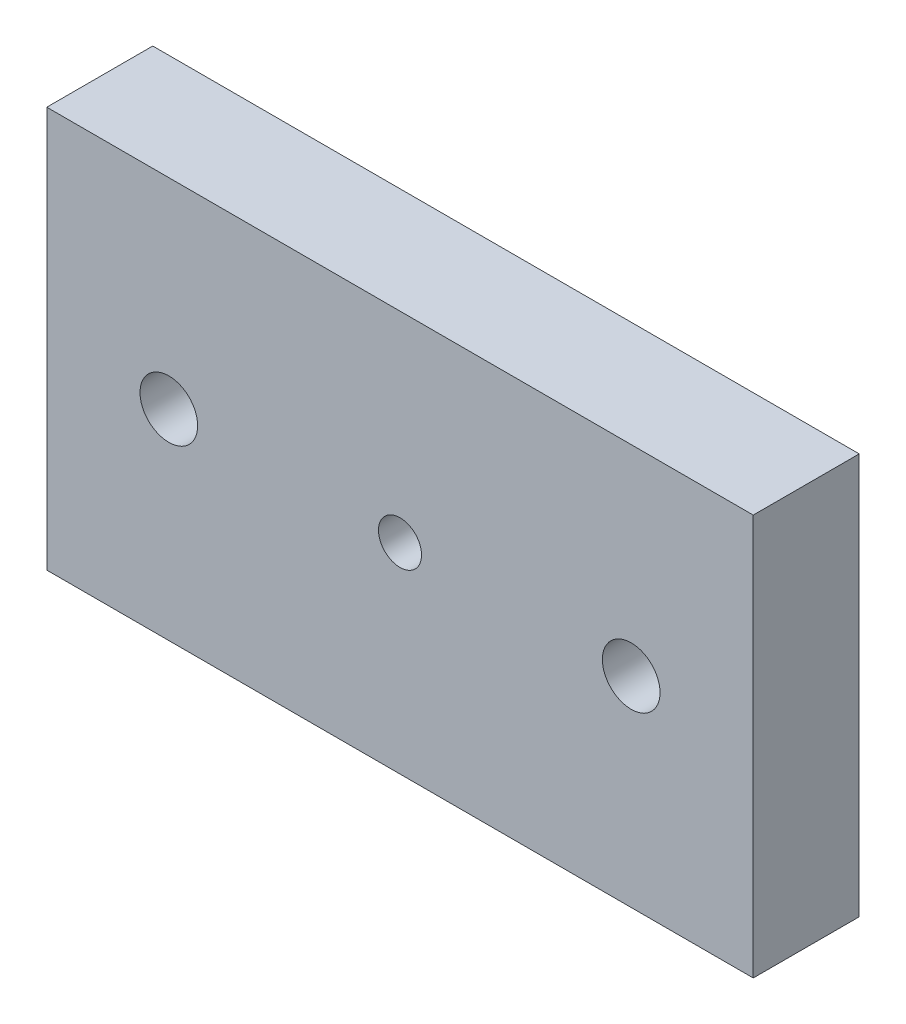
SolidWorks part; units mm, degrees
ref_plane "Front Plane" through (0, 0, 0) normal (0, 0, 1) x (1, 0, 0)
ref_plane "Top Plane" through (0, 0, 0) normal (0, 1, 0) x (1, 0, 0)
ref_plane "Right Plane" through (0, 0, 0) normal (1, 0, 0) x (0, 0, -1)
sketch "Sketch1" plane through (0, 0, 0) normal (0, 0, 1) x (1, 0, 0)
  line L1 (-20, 11.35) -> (20, 11.35)
  line L2 (-20, 11.35) -> (-20, -11.35)
  line L3 (-20, -11.35) -> (20, -11.35)
  line L4 (20, 11.35) -> (20, -11.35)
  line L5 (-20, 11.35) -> (20, -11.35) construction
  line L6 (-20, -11.35) -> (20, 11.35) construction
  point P0 (0, 0)
  dimension "D1" = 22.7
  dimension "D2" = 40
extrude "Boss-Extrude1" add sketch "Sketch1" against normal blind 6
hole_wizard "#4 Clearance Hole1" positions "Sketch2" profile "Sketch3" hole size "#4" standard "ANSI Inch" end condition through all
sketch "Sketch2" plane through (0, 0, 0) normal (0, 0, 1) x (1, 0, 0)
  point P0 (-13.09, 0)
  point P2 (13.09, 0)
  dimension "D1" = 26.18
  dimension "D2" = 13.09
sketch "Sketch3" plane through (-13.09, 0, 0) normal (1, 0, 0) x (0, -1, 0)
  line L0 (0, 0) -> (0, 6)
  line L1 (0, 6) -> (1.6319, 6)
  line L2 (1.6319, 6) -> (1.6319, 0)
  line L5 (1.6319, 0) -> (0, 0)
  line L11 (0, -6.35) -> (0, 107.95) construction
  dimension "Thru Hole Dia." = 3.2639
  dimension "Thru Hole Depth" = 6
hole_wizard "#2 Clearance Hole1" positions "Sketch4" profile "Sketch5" hole size "#2" standard "ANSI Inch" end condition through all
sketch "Sketch4" plane through (0, 0, 0) normal (0, 0, 1) x (1, 0, 0)
  point P0 (0, 0)
sketch "Sketch5" plane through (0, 0, 0) normal (1, 0, 0) x (0, -1, 0)
  line L0 (0, 0) -> (0, 6)
  line L1 (0, 6) -> (1.2192, 6)
  line L2 (1.2192, 6) -> (1.2192, 0)
  line L5 (1.2192, 0) -> (0, 0)
  line L11 (0, -6.35) -> (0, 107.95) construction
  dimension "Thru Hole Dia." = 2.4384
  dimension "Thru Hole Depth" = 6
equation "\"D2@Sketch2\"=\"D1@Sketch2\"/2"
